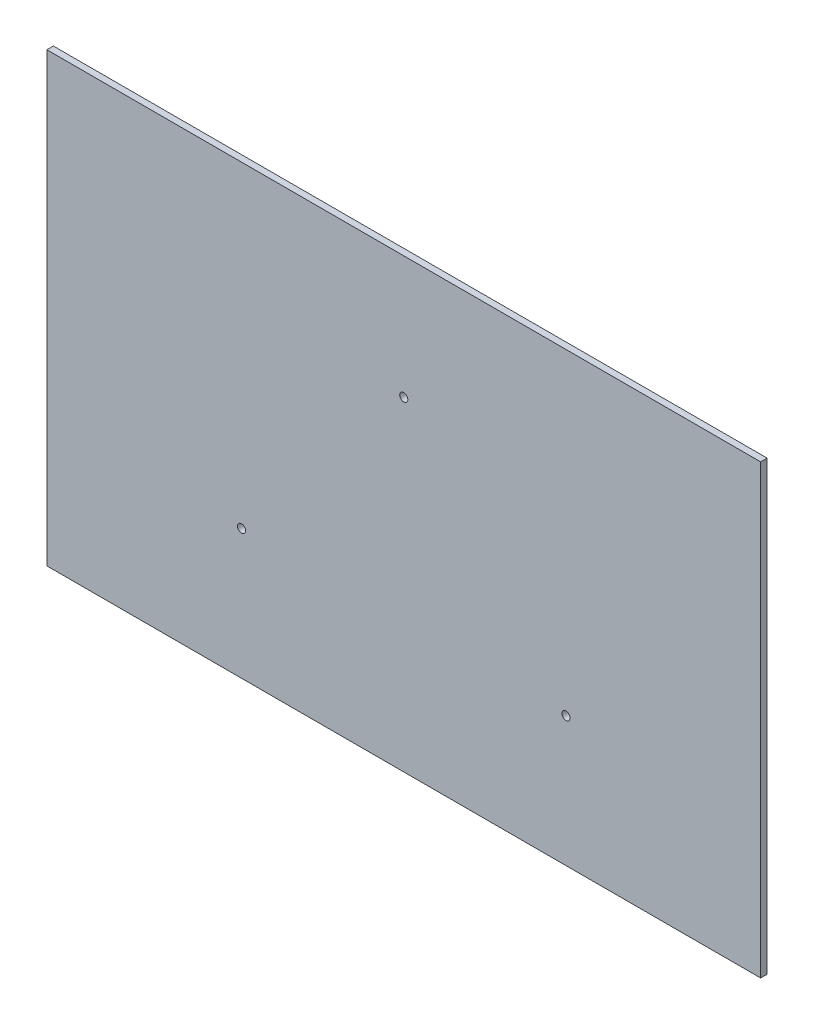
SolidWorks part; units mm, degrees
material "1.5918 (17CrNi6-6)"
ref_plane "Front Plane" through (0, 0, 0) normal (0, 0, 1) x (1, 0, 0)
ref_plane "Top Plane" through (0, 0, 0) normal (0, 1, 0) x (1, 0, 0)
ref_plane "Right Plane" through (0, 0, 0) normal (1, 0, 0) x (0, 0, -1)
sketch "Sketch2" plane through (0, 0, 0) normal (0, 0, 1) x (1, 0, 0)
  line L1 (139.7, -87.4889) -> (-139.7, -87.4889)
  line L2 (139.7, -87.4889) -> (139.7, 87.4889)
  line L3 (139.7, 87.4889) -> (-139.7, 87.4889)
  line L4 (-139.7, -87.4889) -> (-139.7, 87.4889)
  line L5 (139.7, -87.4889) -> (-139.7, 87.4889) construction
  line L6 (139.7, 87.4889) -> (-139.7, -87.4889) construction
  circle A0 centre (-63.5, -36.6889) radius 1.5875
  circle A1 centre (63.5, -36.6889) radius 1.5875
  circle A2 centre (0, 39.5111) radius 1.5875
  point P0 (0, 0)
  dimension "D2" = 3.175
  dimension "D1" = 279.4
  dimension "D3" = 76.2
  dimension "D4" = 203.2
  dimension "D5" = 50.8
  dimension "D6" = 50.8
  dimension "D7" = 127
  dimension "D8" = 139.7
extrude "Boss-Extrude1" add sketch "Sketch2" along normal blind 2.54
